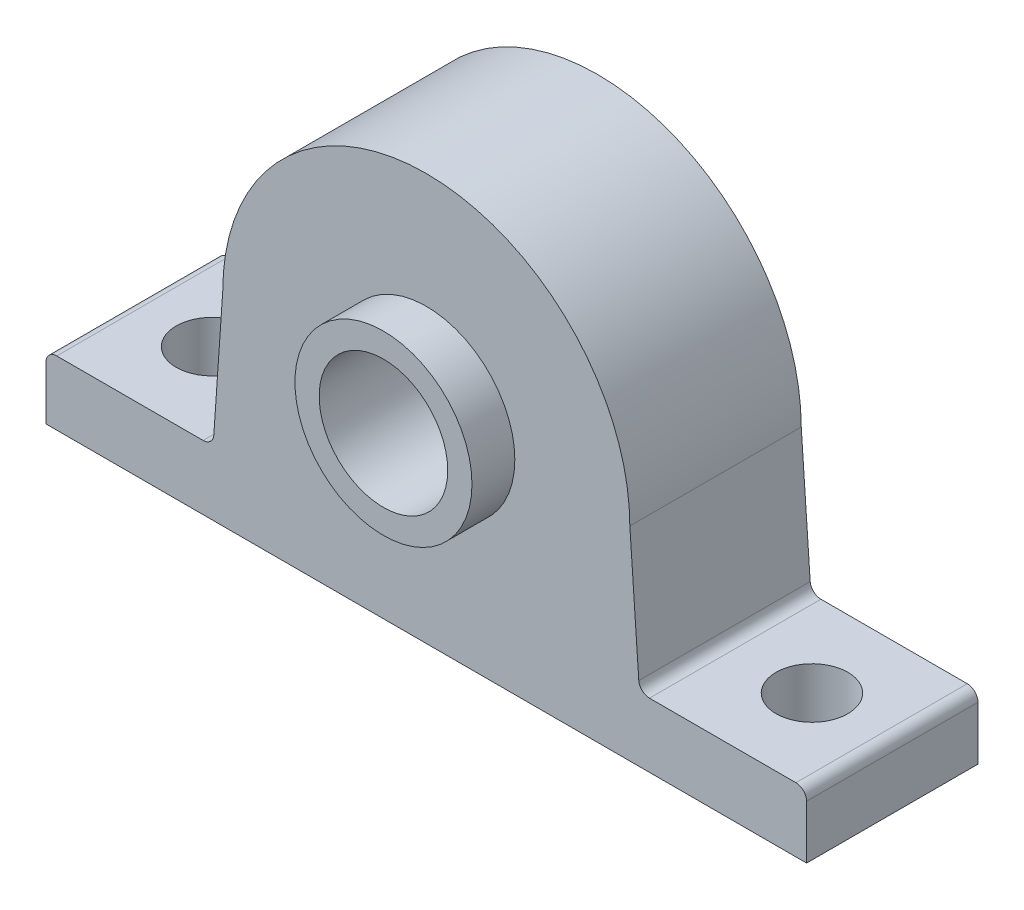
SolidWorks part; units mm, degrees
ref_plane "Front Plane" through (0, 0, 0) normal (0, 0, 1) x (1, 0, 0)
ref_plane "Top Plane" through (0, 0, 0) normal (0, 1, 0) x (1, 0, 0)
ref_plane "Right Plane" through (0, 0, 0) normal (1, 0, 0) x (0, 0, -1)
sketch "Sketch1" plane through (0, 0, 0) normal (0, 0, 1) x (1, 0, 0)
  line L0 (0, -19) -> (-35.5, -19) construction
  line L1 (-35.5, -19) -> (-35.5, -13)
  line L2 (-35.5, -19) -> (35.5, -19)
  line L3 (-35.5, -13) -> (-19.9, -13)
  line L4 (-19.9, -13) -> (-19, 0)
  line L5 (0, 0) -> (0, -19) construction
  line L6 (35.5, -19) -> (35.5, -13)
  line L7 (35.5, -13) -> (19.9, -13)
  line L8 (19.9, -13) -> (19, 0)
  circle A0 centre (0, 0) radius 6
  circle A1 centre (0, 0) radius 19
  dimension "D1" = 12
  dimension "D2" = 38
  dimension "D3" = 35.5
  dimension "D4" = 6
  dimension "D6" = 15.6
extrude "Boss-Extrude1" add sketch "Sketch1" along normal blind 16 contours A1 L4 L3 L1 L2 | A1 A0 | A1 L2 L6 L7 L8
sketch "Sketch2" plane through (0, 0, 16) normal (0, 0, 1) x (1, 0, 0)
  circle A0 centre (0, 0) radius 8.265
  circle A1 centre (0, 0) radius 6
  dimension "D1" = 16.53
  dimension "D2" = 12
extrude "Boss-Extrude2" add sketch "Sketch2" along normal blind 4
fillet "Fillet1" radius 1 4 edges at (-19.9, -13, 8) (-35.5, -13, 8) (35.5, -13, 8) (19.9, -13, 8)
sketch "Sketch3" plane through (0, -19, 0) normal (0, -1, 0) x (1, 0, 0)
  line L0 (0, 16) -> (0, 8) construction
  line L1 (-35.5, 16) -> (35.5, 16) construction
  line L2 (0, 8) -> (28, 8) construction
  circle A0 centre (28, 8) radius 3.35
  circle A1 centre (-28, 8) radius 3.35
  dimension "D3" = 6.7
  dimension "D1" = 8
  dimension "D2" = 28
extrude "Cut-Extrude1" cut sketch "Sketch3" against normal up to next
